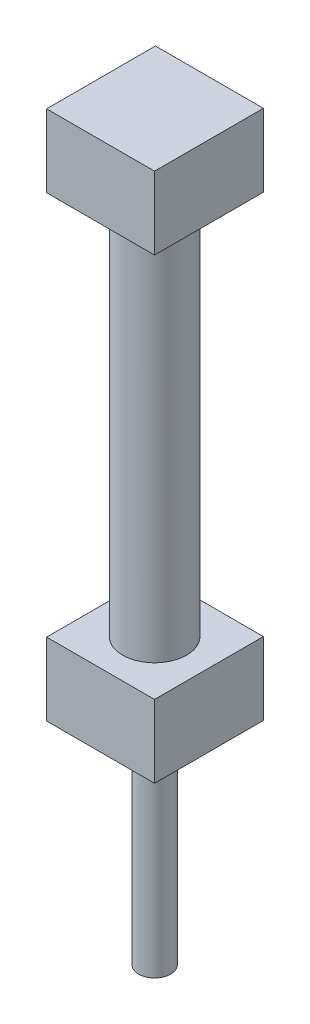
SolidWorks part; units mm, degrees
ref_plane "Front Plane" through (0, 0, 0) normal (0, 0, 1) x (1, 0, 0)
ref_plane "Top Plane" through (0, 0, 0) normal (0, 1, 0) x (1, 0, 0)
ref_plane "Right Plane" through (0, 0, 0) normal (1, 0, 0) x (0, 0, -1)
sketch "Sketch1" plane through (0, 0, 0) normal (0, 1, 0) x (1, 0, 0)
  circle A0 centre (0, 0) radius 15
  dimension "D1" = 30
extrude "Boss-Extrude2" add sketch "Sketch1" along normal blind 194
sketch "Sketch2" plane through (0, 0, 0) normal (0, -1, 0) x (1, 0, 0)
  line L1 (-25.062, -25.4577) -> (25.4137, -25.4577)
  line L2 (-25.062, -25.4577) -> (-25.062, 25.4577)
  line L3 (-25.062, 25.4577) -> (25.4137, 25.4577)
  line L4 (25.4137, -25.4577) -> (25.4137, 25.4577)
extrude "Boss-Extrude3" add sketch "Sketch2" along normal blind 34
ref_plane "Plane1" through (0, 90, 0) normal (0, 1, 0) x (1, 0, 0)
mirror "Mirror1" about plane through (0, 90, 0) normal (0, 1, 0) of "Boss-Extrude3"
sketch "Sketch3" plane through (0, -34, 0) normal (0, -1, 0) x (1, 0, 0)
  circle A0 centre (0, 0) radius 7.5
  dimension "D1" = 15
extrude "Boss-Extrude4" add sketch "Sketch3" along normal blind 99
sketch "Sketch4" plane through (0, 0, 25.4577) normal (0, 0, 1) x (1, 0, 0)
  circle A0 centre (-1.3007, -17.8609) radius 6.5278
  circle A1 centre (0, 196.9149) radius 7.2734
